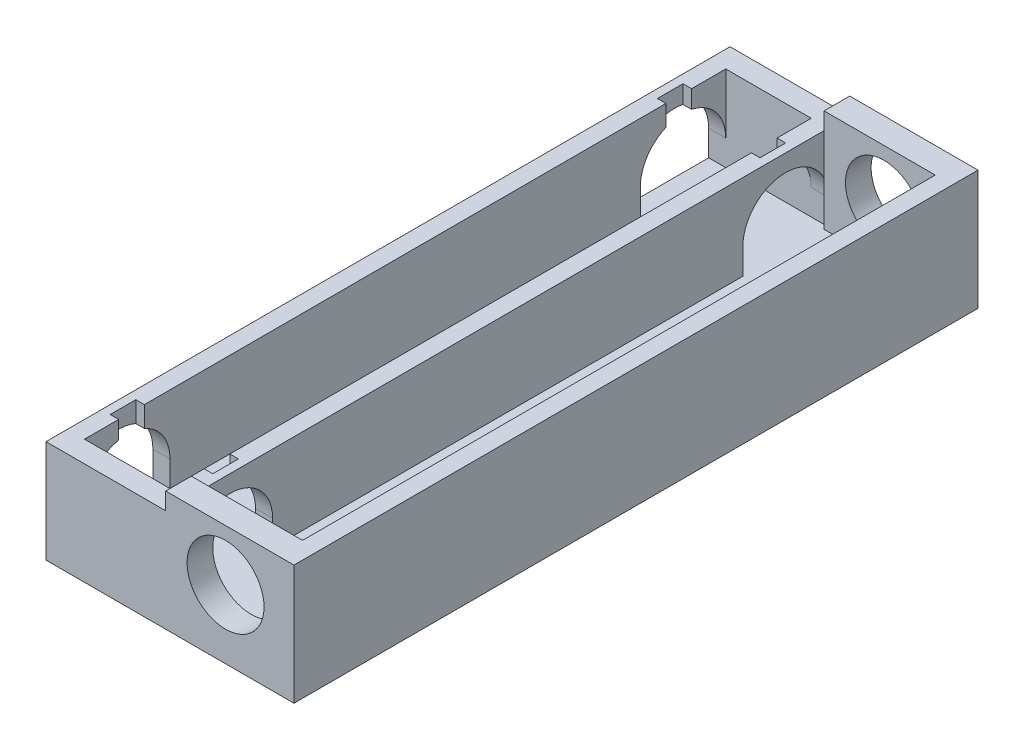
SolidWorks part; units mm, degrees
ref_plane "Front Plane" through (0, 0, 0) normal (0, 0, 1) x (1, 0, 0)
ref_plane "Top Plane" through (0, 0, 0) normal (0, 1, 0) x (1, 0, 0)
ref_plane "Right Plane" through (0, 0, 0) normal (1, 0, 0) x (0, 0, -1)
sketch "Sketch1" plane through (0, 0, 0) normal (0, 1, 0) x (1, 0, 0)
  line L1 (-7, -40) -> (7, -40)
  line L2 (-7, -40) -> (-7, 40)
  line L3 (-7, 40) -> (7, 40)
  line L4 (7, -40) -> (7, 40)
  line L5 (-7, -40) -> (7, 40) construction
  line L6 (-7, 40) -> (7, -40) construction
  point P0 (0, 0)
  dimension "D1" = 80
  dimension "D2" = 14
extrude "Boss-Extrude1" add sketch "Sketch1" along normal blind 2
sketch "Sketch2" plane through (0, 2, 0) normal (0, 1, 0) x (1, 0, 0)
  line L1 (-5, -37.5) -> (5, -37.5)
  line L2 (-5, -37.5) -> (-5, 37.5)
  line L3 (-5, 37.5) -> (5, 37.5)
  line L4 (5, -37.5) -> (5, 37.5)
  line L5 (-5, -37.5) -> (5, 37.5) construction
  line L6 (-5, 37.5) -> (5, -37.5) construction
  line L7 (7, -40) -> (-7, -40)
  line L8 (7, -40) -> (7, 40)
  line L9 (7, 40) -> (-7, 40)
  line L10 (-7, -40) -> (-7, 40)
  line L11 (7, -40) -> (-7, 40) construction
  line L12 (7, 40) -> (-7, -40) construction
  point P0 (0, 0)
  point P6 (0, 0)
  dimension "D1" = 75
  dimension "D2" = 10
extrude "Boss-Extrude2" add sketch "Sketch2" along normal blind 10
sketch "Sketch3" plane through (0, 12, 0) normal (0, 1, 0) x (1, 0, 0)
  line L0 (0, 0) -> (0, 37.5) construction
  line L1 (5, 37.5) -> (-5, 37.5) construction
  line L2 (0, 37.5) -> (5, 37.5) construction
  line L3 (5, 37.5) -> (5, 33.5) construction
  line L4 (-5, 37.5) -> (-5, 33.5) construction
  line L5 (0, 0) -> (0, -37.5) construction
  line L6 (-5, -37.5) -> (5, -37.5) construction
  line L7 (0, -37.5) -> (5, -37.5) construction
  line L8 (0, -37.5) -> (-5, -37.5) construction
  line L9 (-5, -37.5) -> (-5, -33.5) construction
  line L10 (5, -37.5) -> (5, -33.5) construction
  line L12 (-5, -33.5) -> (-6, -33.5)
  line L13 (-5, -33.5) -> (-5, -30.5)
  line L14 (-5, -30.5) -> (-6, -30.5)
  line L15 (-6, -33.5) -> (-6, -30.5)
  line L16 (5, -33.5) -> (6, -33.5)
  line L17 (5, -33.5) -> (5, -30.5)
  line L18 (5, -30.5) -> (6, -30.5)
  line L19 (6, -33.5) -> (6, -30.5)
  line L20 (5, 33.5) -> (6, 33.5)
  line L21 (5, 33.5) -> (5, 30.5)
  line L22 (5, 30.5) -> (6, 30.5)
  line L23 (6, 33.5) -> (6, 30.5)
  line L24 (-5, 33.5) -> (-6, 33.5)
  line L25 (-5, 33.5) -> (-5, 30.5)
  line L26 (-5, 30.5) -> (-6, 30.5)
  line L27 (-6, 33.5) -> (-6, 30.5)
  dimension "D1" = 4
  dimension "D2" = 1
  dimension "D3" = 3
extrude "Cut-Extrude1" cut sketch "Sketch3" against normal blind 10
sketch "Sketch4" plane through (7, 0, 0) normal (1, 0, 0) x (0, 0, -1)
  line L0 (0, 0) -> (0, 2) construction
  line L1 (-40, 0) -> (40, 0) construction
  line L2 (0, 2) -> (-32.5, 2) construction
  line L3 (-32.5, 2) -> (-32.5, 5) construction
  line L4 (0, 2) -> (32.5, 2) construction
  line L5 (32.5, 2) -> (32.5, 5) construction
  line L6 (32.5, 2) -> (37.5, 2)
  line L7 (37.5, 2) -> (37.5, 5)
  line L8 (-32.5, 2) -> (-37.5, 2)
  line L9 (-37.5, 2) -> (-37.5, 5)
  line L10 (-32.5, 2) -> (-27.5, 2)
  line L11 (32.5, 2) -> (27.5, 2)
  line L12 (-27.5, 2) -> (-27.5, 5)
  line L13 (27.5, 2) -> (27.5, 5)
  arc A0 (27.5, 5) -> (37.5, 5) centre (32.5, 5) cw
  arc A1 (-37.5, 5) -> (-27.5, 5) centre (-32.5, 5) cw
  dimension "D1" = 2
  dimension "D2" = 32.5
  dimension "D3" = 3
  dimension "D4" = 5
extrude "Cut-Extrude2" cut sketch "Sketch4" against normal blind 14 contours A1 L9 L8 L10 L12 | A0 L13 L11 L6 L7
sketch "Sketch5" plane through (0, 0, 0) normal (0, 1, 0) x (1, 0, 0)
  line L0 (0, 0) -> (7, 0) construction
  line L1 (7, -40) -> (7, 40) construction
  line L2 (7, 0) -> (7, -40) construction
  line L4 (7, -40) -> (22, -40)
  line L5 (7, -40) -> (7, 40)
  line L6 (7, 40) -> (22, 40)
  line L7 (22, -40) -> (22, 40)
  dimension "D1" = 80
  dimension "D2" = 15
extrude "Boss-Extrude3" add sketch "Sketch5" along normal blind 2
sketch "Sketch6" plane through (0, 2, 0) normal (0, 1, 0) x (1, 0, 0)
  line L0 (22, -40) -> (22, 40) construction
  line L1 (7, -40) -> (22, -40)
  line L2 (7, -40) -> (7, -37)
  line L3 (7, -37) -> (22, -37)
  line L4 (22, -40) -> (22, -37)
  line L6 (7, 40) -> (22, 40)
  line L7 (7, 40) -> (7, 37)
  line L8 (7, 37) -> (22, 37)
  line L9 (22, 40) -> (22, 37)
  dimension "D1" = 3
  dimension "D2" = 3
extrude "Boss-Extrude4" add sketch "Sketch6" along normal blind 12
sketch "Sketch7" plane through (0, 0, 40) normal (0, 0, 1) x (1, 0, 0)
  line L0 (0, 0) -> (7.5, 0) construction
  line L1 (-7, 0) -> (22, 0) construction
  line L2 (7.5, 0) -> (14, 0) construction
  line L3 (14, 0) -> (14, 8) construction
  circle A0 centre (14, 8) radius 4.5
  dimension "D3" = 9
  dimension "D1" = 6.5
  dimension "D2" = 8
extrude "Cut-Extrude3" cut sketch "Sketch7" against normal blind 80
sketch "Sketch8" plane through (0, 2, 0) normal (0, 1, 0) x (1, 0, 0)
  line L0 (22, -37) -> (7, -37) construction
  line L5 (22, 37) -> (20, 37)
  line L6 (22, 37) -> (22, -37)
  line L7 (22, -37) -> (20, -37)
  line L8 (20, 37) -> (20, -37)
  dimension "D1" = 2
extrude "Boss-Extrude5" add sketch "Sketch8" along normal blind 12
